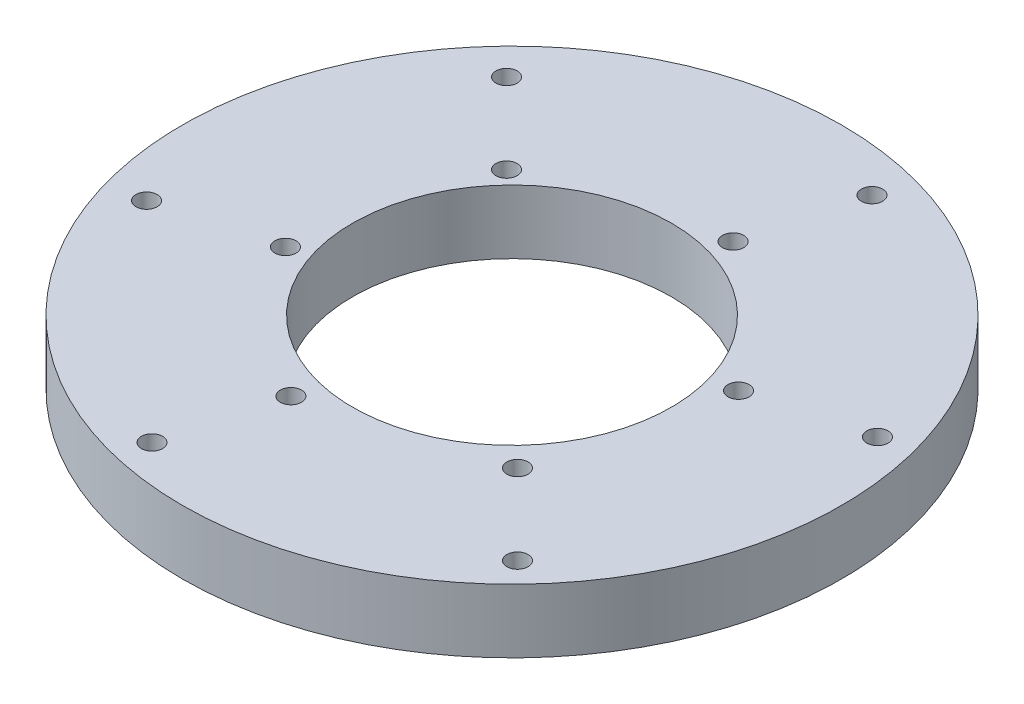
SolidWorks part; units mm, degrees
ref_plane "Front" through (0, 0, 0) normal (0, 0, 1) x (1, 0, 0)
ref_plane "Top" through (0, 0, 0) normal (0, 1, 0) x (1, 0, 0)
ref_plane "Right" through (0, 0, 0) normal (1, 0, 0) x (0, 0, -1)
sketch "Sketch1" plane through (0, 0, 0) normal (0, 1, 0) x (1, 0, 0)
  circle A0 centre (0, 0) radius 98.425
  circle A1 centre (0, 0) radius 47.625
  dimension "D1" = 196.85
  dimension "D2" = 95.25
extrude "Boss-Extrude1" add sketch "Sketch1" along normal blind 19.05
sketch "Sketch2" plane through (0, 19.05, 0) normal (0, 1, 0) x (1, 0, 0)
  line L0 (0, 0) -> (94.0634, 25.2042) construction
  line L1 (100.8168, 0) -> (87.31, 50.4084) construction
  line L2 (40.5098, 70.1649) -> (0, 81.0195) construction
  circle A0 centre (0, 0) radius 55.245 construction
  circle A1 centre (0, 0) radius 89.1181 construction
  circle A2 centre (53.3626, 14.2985) radius 3.175
  circle A3 centre (86.0814, 23.0655) radius 3.175
  circle A4 centre (40.3529, -38.7188) radius 3.175
  circle A5 centre (64.3048, -62.6707) radius 3.175
  circle A6 centre (-12.0662, -53.9607) radius 3.175
  circle A7 centre (-20.8332, -86.6796) radius 3.175
  circle A8 centre (-51.4757, -16.1854) radius 3.175
  circle A9 centre (-84.1945, -24.9524) radius 3.175
  circle A10 centre (-38.466, 36.8319) radius 3.175
  circle A11 centre (-62.4179, 60.7838) radius 3.175
  circle A12 centre (13.9531, 52.0738) radius 3.175
  circle A13 centre (22.7201, 84.7927) radius 3.175
  point P33 (0.9435, -0.9435)
  dimension "D1" = 6.35
  dimension "D2" = 6.35
  dimension "D3" = 110.49
  dimension "D4" = 9.525
extrude "Cut-Extrude1" cut sketch "Sketch2" against normal blind 19.05
